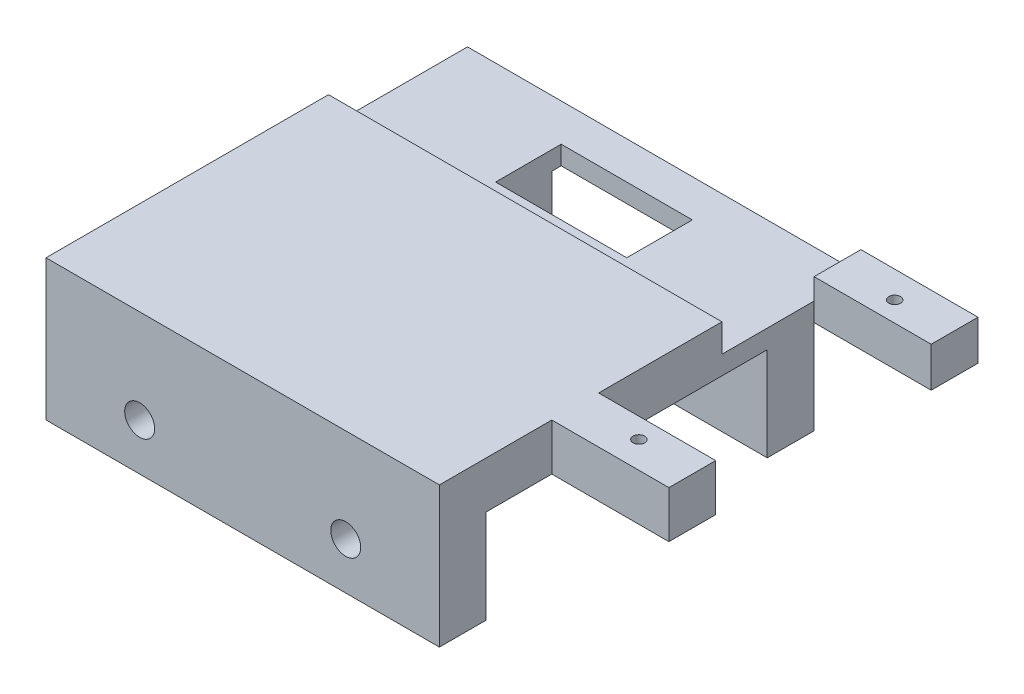
SolidWorks part; units mm, degrees
ref_plane "前视基准面" through (0, 0, 0) normal (0, 0, 1) x (1, 0, 0)
ref_plane "上视基准面" through (0, 0, 0) normal (0, 1, 0) x (1, 0, 0)
ref_plane "右视基准面" through (0, 0, 0) normal (1, 0, 0) x (0, 0, -1)
sketch "草图1" plane through (0, 0, 0) normal (0, 1, 0) x (1, 0, 0)
  line L1 (0, 0) -> (42, 0)
  line L2 (0, 0) -> (0, -45)
  line L3 (0, -45) -> (42, -45)
  line L4 (42, 0) -> (42, -45)
  line L5 (0, 0) -> (42, -45) construction
  line L6 (0, -45) -> (42, 0) construction
  point P4 (21, -22.5)
  dimension "D1" = 42
  dimension "D2" = 45
extrude "凸台-拉伸1" add sketch "草图1" along normal blind 5
sketch "草图2" plane through (0, 0, 0) normal (0, -1, 0) x (1, 0, 0)
  line L0 (42, 45) -> (42, 0) construction
  line L1 (0, 45) -> (42, 45)
  line L2 (0, 45) -> (0, 40)
  line L3 (0, 40) -> (42, 40)
  line L4 (42, 45) -> (42, 40)
  line L5 (0, 45) -> (42, 40) construction
  line L6 (0, 40) -> (42, 45) construction
  line L7 (0, 0) -> (0, 45) construction
  line L8 (0, 10) -> (42, 10)
  line L9 (0, 10) -> (0, 5)
  line L10 (0, 5) -> (42, 5)
  line L11 (42, 10) -> (42, 5)
  line L12 (0, 10) -> (42, 5) construction
  line L13 (0, 5) -> (42, 10) construction
  point P4 (21, 42.5)
  point P12 (21, 7.5)
  dimension "D1" = 5
  dimension "D2" = 5
  dimension "D3" = 30
extrude "凸台-拉伸2" add sketch "草图2" along normal blind 10
sketch "草图3" plane through (0, 0, 5) normal (0, 0, -1) x (-1, 0, 0)
  line L0 (-42, -5) -> (0, -5) construction
  line L1 (-42, -10) -> (-42, 0) construction
  line L2 (0, -10) -> (0, 0) construction
  circle A0 centre (-32, -5) radius 1.6
  circle A1 centre (-10, -5) radius 1.6
  dimension "D1" = 3.2
  dimension "D2" = 3.2
  dimension "D3" = 10
  dimension "D4" = 10
extrude "切除-拉伸1" cut sketch "草图3" against normal through all
sketch "草图4" plane through (0, -10, 0) normal (0, -1, 0) x (1, 0, 0)
  line L0 (21, 45) -> (21, 0) construction
  line L1 (42, 45) -> (0, 45) construction
  line L2 (42, 0) -> (0, 0) construction
  line L4 (14, 11) -> (28, 11)
  line L5 (14, 11) -> (14, 4)
  line L6 (14, 4) -> (28, 4)
  line L7 (28, 11) -> (28, 4)
  line L8 (21, 4) -> (21, 11) construction
  line L9 (14, 7.5) -> (28, 7.5) construction
  point P6 (21, 7.5)
  dimension "D1" = 7
  dimension "D2" = 14
extrude "切除-拉伸2" cut sketch "草图4" against normal through all
sketch "草图5" plane through (0, 5, 0) normal (0, 1, 0) x (1, 0, 0)
  line L0 (42, -45) -> (42, 0) construction
  line L1 (0, 0) -> (42, 0)
  line L2 (0, 0) -> (0, -14.8381)
  line L3 (0, -14.8381) -> (42, -14.8381)
  line L4 (42, 0) -> (42, -14.8381)
  line L5 (0, 0) -> (42, -14.8381) construction
  line L6 (0, -14.8381) -> (42, 0) construction
  point P4 (21, -7.4191)
extrude "切除-拉伸3" cut sketch "草图5" against normal blind 3
sketch "草图6" plane through (0, 0, 0) normal (0, -1, 0) x (1, 0, 0)
  line L1 (0, 10) -> (5, 10)
  line L2 (0, 10) -> (0, 40)
  line L3 (0, 40) -> (5, 40)
  line L4 (5, 10) -> (5, 40)
  line L5 (0, 10) -> (5, 40) construction
  line L6 (0, 40) -> (5, 10) construction
  point P4 (2.5, 25)
  dimension "D1" = 5
extrude "凸台-拉伸3" add sketch "草图6" along normal blind 10
sketch "草图7" plane through (5, 0, 0) normal (1, 0, 0) x (0, 0, -1)
  line L0 (-40, -5) -> (-10, -5) construction
  line L1 (-40, -10) -> (-40, 0) construction
  line L2 (-10, -10) -> (-10, 0) construction
  circle A0 centre (-35, -5) radius 1.75
  circle A1 centre (-15, -5) radius 1.75
  point P10 (0, 0)
  point P11 (0, 0)
  point P12 (0, 0)
  point P14 (-35.2117, -6.7371)
  point P15 (-15.6727, -6.1459)
  dimension "D1" = 3.5
  dimension "D2" = 3.5
  dimension "D3" = 5
  dimension "D4" = 20
extrude "切除-拉伸4" cut sketch "草图7" against normal through all
sketch "草图8" plane through (5, 0, 0) normal (1, 0, 0) x (0, 0, -1)
  circle A0 centre (-35, -5) radius 3.5
  dimension "D1" = 7
extrude "切除-拉伸5" cut sketch "草图8" against normal blind 2
sketch "草图9" plane through (42, 0, 0) normal (1, 0, 0) x (0, 0, -1)
  line L0 (-40, 0) -> (-10, 0) construction
  line L1 (-33, 0) -> (-28, 0)
  line L2 (-33, 0) -> (-33, 5)
  line L3 (-33, 5) -> (-28, 5)
  line L4 (-28, 0) -> (-28, 5)
  line L5 (-33, 0) -> (-28, 5) construction
  line L6 (-33, 5) -> (-28, 0) construction
  line L7 (-45, 5) -> (-14.8381, 5) construction
  line L9 (-5, 0) -> (0, 0)
  line L10 (-5, 0) -> (-5, 4.2551)
  line L11 (-5, 4.2551) -> (0, 4.2551)
  line L12 (0, 0) -> (0, 4.2551)
  line L13 (-5, 0) -> (0, 4.2551) construction
  line L14 (-5, 4.2551) -> (0, 0) construction
  point P4 (-30.5, 2.5)
  point P13 (-2.5, 2.1275)
  dimension "D1" = 5
  dimension "D2" = 5
  dimension "D3" = 23
extrude "凸台-拉伸4" add sketch "草图9" along normal blind 12.5
sketch "草图10" plane through (0, 0, 0) normal (0, -1, 0) x (1, 0, 0)
  circle A0 centre (48.45, 30.15) radius 0.625
  circle A1 centre (48.45, 2.85) radius 0.625
extrude "切除-拉伸6" cut sketch "草图10" against normal through all
